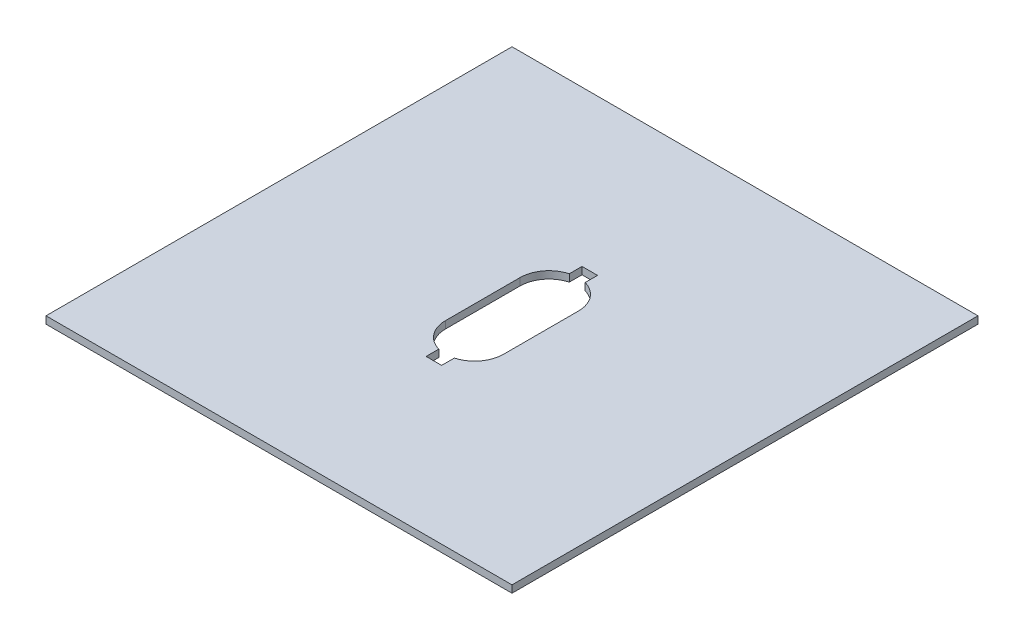
SolidWorks part; units mm, degrees
material "Plastique personnalisé"
ref_plane "Plan de face" through (0, 0, 0) normal (0, 0, 1) x (1, 0, 0)
ref_plane "Plan de dessus" through (0, 0, 0) normal (0, 1, 0) x (1, 0, 0)
ref_plane "Plan de droite" through (0, 0, 0) normal (1, 0, 0) x (0, 0, -1)
sketch "Esquisse1" plane through (0, 0, 0) normal (0, 1, 0) x (1, 0, 0)
  line L1 (-152.4, -152.4) -> (152.4, -152.4)
  line L2 (-152.4, -152.4) -> (-152.4, 152.4)
  line L3 (-152.4, 152.4) -> (152.4, 152.4)
  line L4 (152.4, -152.4) -> (152.4, 152.4)
  line L5 (-152.4, -152.4) -> (152.4, 152.4) construction
  line L6 (-152.4, 152.4) -> (152.4, -152.4) construction
  point P0 (0, 0)
  dimension "D1" = 304.8
  dimension "D2" = 304.8
extrude "Boss.-Extru.1" add sketch "Esquisse1" along normal mid plane 4.7625
sketch "Esquisse2" plane through (0, 2.3813, 0) normal (0, 1, 0) x (1, 0, 0)
  line L0 (-5.08, -51.106) -> (5.08, -51.106)
  line L1 (5.08, -51.106) -> (5.08, -42.7953)
  line L2 (19.0246, -24.4614) -> (19.0246, 24.4614)
  line L3 (5.08, 42.7953) -> (5.08, 50.875)
  line L4 (5.08, 50.875) -> (-5.08, 50.875)
  line L5 (-5.08, 50.875) -> (-5.08, 42.5642)
  line L6 (-19.0246, 24.2304) -> (-19.0246, -24.4614)
  line L7 (-5.08, -42.7953) -> (-5.08, -51.106)
  line L13 (-2.6194, 0) -> (2.6194, 0) construction
  line L14 (0, -2.6194) -> (0, 2.6194) construction
  arc A0 (5.08, -42.7953) -> (19.0246, -24.4614) centre (0, -24.4614) ccw
  arc A1 (19.0246, 24.4614) -> (5.08, 42.7953) centre (0, 24.4614) ccw
  arc A2 (-19.0246, -24.4614) -> (-5.08, -42.7953) centre (0, -24.4614) ccw
  arc A3 (-19.0246, 24.2304) -> (-5.08, 42.5642) centre (0, 24.2304) cw
  point P3 (19.0246, 0)
  point P19 (0, 0)
extrude "Enlèv. mat.-Extru.1" cut sketch "Esquisse2" against normal through all
